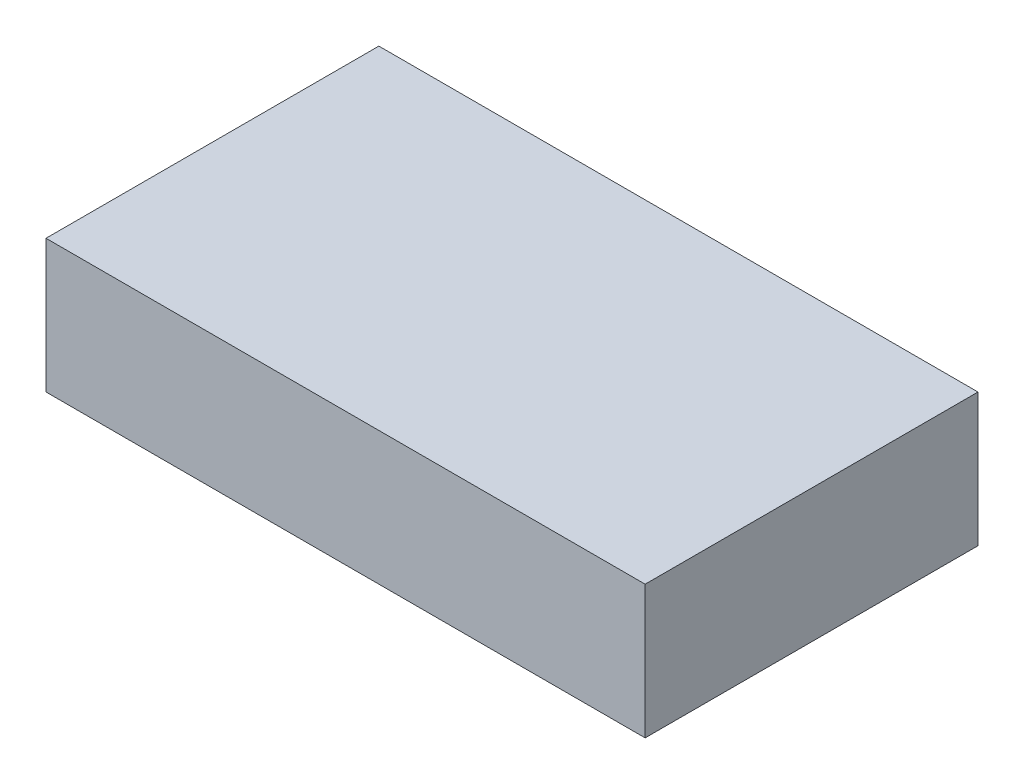
SolidWorks part; units mm, degrees
ref_plane "Front Plane" through (0, 0, 0) normal (0, 0, 1) x (1, 0, 0)
ref_plane "Top Plane" through (0, 0, 0) normal (0, 1, 0) x (1, 0, 0)
ref_plane "Right Plane" through (0, 0, 0) normal (1, 0, 0) x (0, 0, -1)
sketch "Sketch1" plane through (0, 0, 0) normal (0, 1, 0) x (1, 0, 0)
  line L1 (-13.5, 7.5) -> (13.5, 7.5)
  line L2 (-13.5, 7.5) -> (-13.5, -7.5)
  line L3 (-13.5, -7.5) -> (13.5, -7.5)
  line L4 (13.5, 7.5) -> (13.5, -7.5)
  line L5 (-13.5, 7.5) -> (13.5, -7.5) construction
  line L6 (-13.5, -7.5) -> (13.5, 7.5) construction
  point P0 (0, 0)
  dimension "D1" = 27
  dimension "D2" = 15
extrude "Boss-Extrude1" add sketch "Sketch1" along normal blind 6
